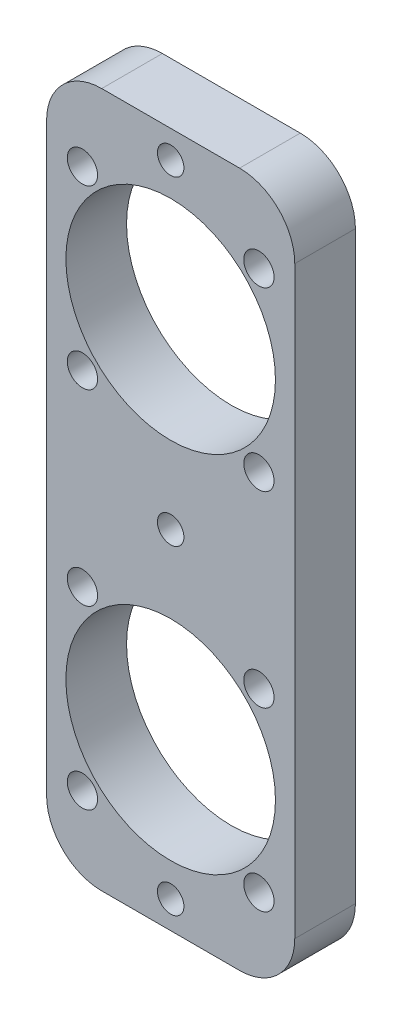
SolidWorks part; units mm, degrees
material "ABS"
ref_plane "X-Y Datum" through (0, 0, 0) normal (0, 0, 1) x (1, 0, 0)
ref_plane "X-Z Datum" through (0, 0, 0) normal (0, 1, 0) x (1, 0, 0)
ref_plane "Y-Z Datum" through (0, 0, 0) normal (1, 0, 0) x (0, 0, -1)
sketch "Sketch1" plane through (0, 0, 0) normal (0, 0, 1) x (1, 0, 0)
  line L0 (0, 30) -> (0, 20) construction
  line L1 (-22.5, 0) -> (22.5, 0) construction
  line L5 (-22.5, -30) -> (22.5, -30)
  line L6 (-22.5, -30) -> (-22.5, 30)
  line L7 (-22.5, 30) -> (22.5, 30)
  line L8 (22.5, -30) -> (22.5, 30)
  line L9 (-22.5, -30) -> (22.5, 30) construction
  line L10 (-22.5, 30) -> (22.5, -30) construction
  line L12 (-22.5, 20) -> (22.5, 20) construction
  circle A0 centre (0, 25) radius 2 construction
  circle A1 centre (0, -25) radius 2 construction
  point P2 (0, 0)
  dimension "D3" = 4
  dimension "D1" = 45
  dimension "D2" = 60
  dimension "D4" = 5
extrude "Boss-Extrude1" add sketch "Sketch1" against normal blind 11
sketch "Sketch6" plane through (0, 0, 0) normal (0, 0, 1) x (1, 0, 0)
  circle A0 centre (-16, 16) radius 2.75
  circle A1 centre (16, 16) radius 2.75
  circle A2 centre (16, -16) radius 2.75
  circle A3 centre (-16, -16) radius 2.75
  point P0 (-16, 16)
  point P1 (16, 16)
  point P3 (16, -16)
  point P5 (-16, -16)
  dimension "D1" = 5.5
extrude "Cut-Extrude2" cut sketch "Sketch6" against normal blind 8.5
sketch "Sketch7" plane through (0, 0, 0) normal (0, 0, 1) x (1, 0, 0)
  arc A0 (-19, 0) -> (19, 0) centre (0, 0) ccw construction
  arc A1 (-19, 0) -> (19, 0) centre (0, 0) ccw
  circle A2 centre (0, 0) radius 19
extrude "Cut-Extrude3" cut sketch "Sketch7" against normal through all contours A1 A2
sketch "Sketch11" plane through (0, -30, 0) normal (0, -1, 0) x (1, 0, 0)
  line L4 (-22.5, 0) -> (-22.5, -11)
  line L5 (-22.5, -11) -> (22.5, -11)
  line L6 (22.5, -11) -> (22.5, 0)
  line L7 (22.5, 0) -> (-22.5, 0)
  line L8 (-22.5, 0) -> (-22.5, -11)
  line L9 (-22.5, -11) -> (22.5, -11)
  line L10 (22.5, -11) -> (22.5, 0)
  line L11 (22.5, 0) -> (-22.5, 0)
  dimension "D1" = 0
extrude "Boss-Extrude2" add sketch "Sketch11" along normal blind 6
ref_plane "Plane1" through (0, -33, 0) normal (0, -1, 0) x (-1, 0, 0)
mirror "Mirror1" about plane through (0, -33, 0) normal (0, -1, 0) of "Cut-Extrude3", "Cut-Extrude2", "Boss-Extrude1"
sketch "Sketch12" plane through (0, 0, 0) normal (0, 0, 1) x (1, 0, 0)
  line L0 (0, -96) -> (0, -30)
  line L1 (-22.5, -96) -> (22.5, -96) construction
  line L2 (-22.5, -30) -> (22.5, -30) construction
  line L4 (-22.5, -30) -> (22.5, -30)
  line L5 (22.5, -30) -> (22.5, 30)
  line L6 (22.5, 30) -> (-22.5, 30)
  line L7 (-22.5, 30) -> (-22.5, -30)
  line L8 (-22.5, -30) -> (22.5, -30)
  line L9 (22.5, -30) -> (22.5, 30)
  line L10 (22.5, 30) -> (-22.5, 30)
  line L11 (-22.5, 30) -> (-22.5, -30)
  circle A0 centre (0, -33) radius 2
  circle A1 centre (0, -91) radius 2
  dimension "D2" = 4
  dimension "D4" = 3
  dimension "D3" = 5
  dimension "D1" = 0
hole_wizard "M4 Clearance Hole2" positions "Sketch15" profile "Sketch14" hole size "M4" standard "ANSI Metric" end condition through all
sketch "Sketch15" plane through (0, 0, 0) normal (0, 0, 1) x (1, 0, 0)
  point P0 (0, -91)
  point P3 (0, -33)
  point P6 (0, 25)
sketch "Sketch14" plane through (0, -91, 0) normal (1, 0, 0) x (0, -1, 0)
  line L0 (0, 0) -> (0, 11)
  line L1 (0, 11) -> (2.4, 11)
  line L2 (2.4, 11) -> (2.4, 0)
  line L5 (2.4, 0) -> (0, 0)
  line L11 (0, -6.35) -> (0, 107.95) construction
  dimension "Thru Hole Dia." = 4.8
  dimension "Thru Hole Depth" = 11
fillet "Fillet1" radius 10 4 edges at (-22.5, -96, -5.5) (22.5, -96, -5.5) (22.5, 30, -5.5) (-22.5, 30, -5.5)
